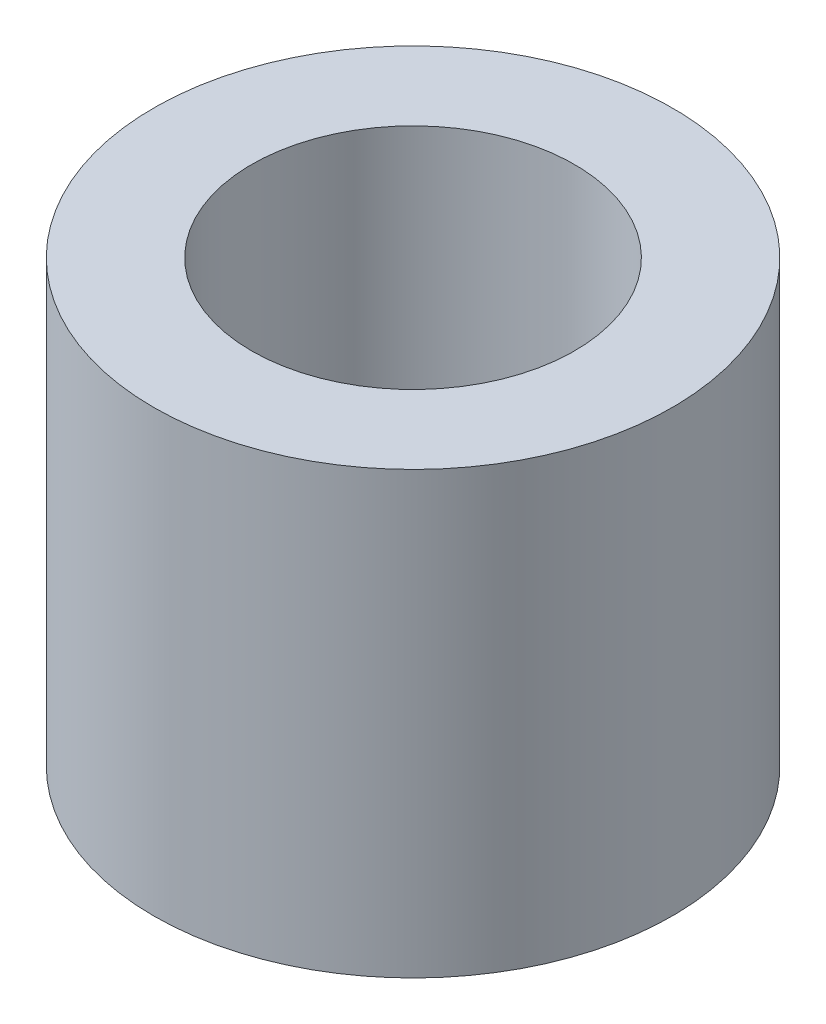
SolidWorks part; units mm, degrees
ref_plane "Front Plane" through (0, 0, 0) normal (0, 0, 1) x (1, 0, 0)
ref_plane "Top Plane" through (0, 0, 0) normal (0, 1, 0) x (1, 0, 0)
ref_plane "Right Plane" through (0, 0, 0) normal (1, 0, 0) x (0, 0, -1)
sketch "Sketch1" plane through (0, 0, 0) normal (0, 1, 0) x (1, 0, 0)
  circle A0 centre (0, 0) radius 1.65
  circle A1 centre (0, 0) radius 2.65
  dimension "D1" = 3.3
  dimension "D2" = 1
extrude "Boss-Extrude1" add sketch "Sketch1" along normal blind 4.5
